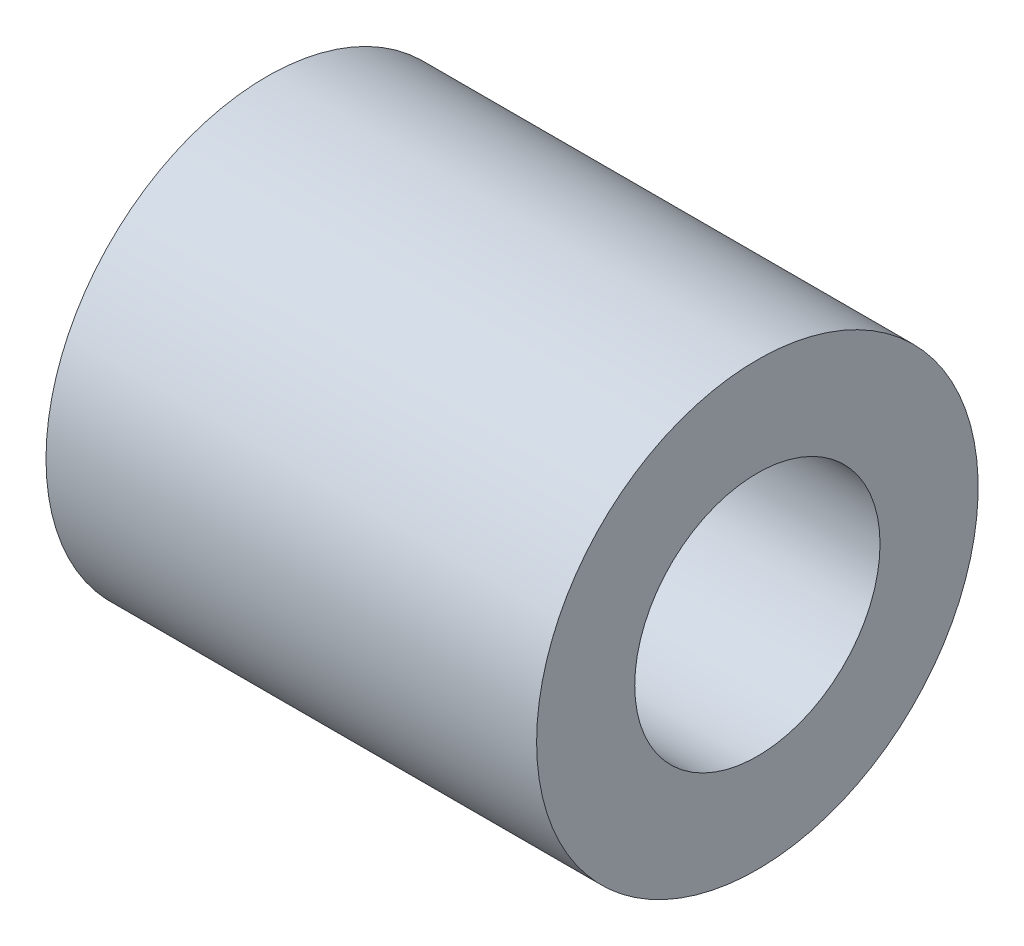
SolidWorks part; units mm, degrees
material "Силиконовая резина"
ref_plane "Спереди" through (0, 0, 0) normal (0, 0, 1) x (1, 0, 0)
ref_plane "Сверху" through (0, 0, 0) normal (0, 1, 0) x (1, 0, 0)
ref_plane "Справа" through (0, 0, 0) normal (1, 0, 0) x (0, 0, -1)
sketch "Эскиз1" plane through (0, 0, 0) normal (0, 0, 1) x (1, 0, 0)
  line L0 (0, 37.5) -> (150, 37.5)
  line L1 (0, 0) -> (80, 0) construction
  line L2 (0, 37.5) -> (0, 67.5)
  line L3 (0, 67.5) -> (150, 67.5)
  line L4 (150, 37.5) -> (150, 67.5)
  dimension "D1" = 150
  dimension "D2" = 67.5
  dimension "D3" = 75
revolve "Повернуть1" add sketch "Эскиз1" angle 360 about L1
